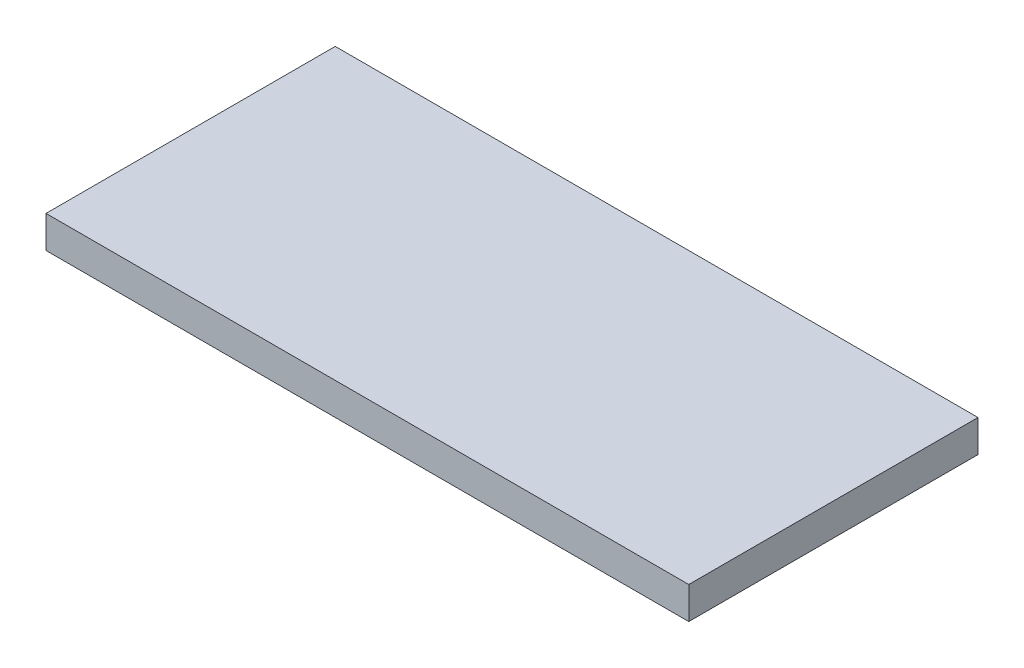
SolidWorks part; units mm, degrees
ref_plane "前视基准面" through (0, 0, 0) normal (0, 0, 1) x (1, 0, 0)
ref_plane "上视基准面" through (0, 0, 0) normal (0, 1, 0) x (1, 0, 0)
ref_plane "右视基准面" through (0, 0, 0) normal (1, 0, 0) x (0, 0, -1)
sketch "草图1" plane through (0, 0, 0) normal (0, 1, 0) x (1, 0, 0)
  line L1 (-50, 22.5) -> (50, 22.5)
  line L2 (-50, 22.5) -> (-50, -22.5)
  line L3 (-50, -22.5) -> (50, -22.5)
  line L4 (50, 22.5) -> (50, -22.5)
  line L5 (-50, 22.5) -> (50, -22.5) construction
  line L6 (-50, -22.5) -> (50, 22.5) construction
  point P0 (0, 0)
  dimension "D1" = 45
  dimension "D2" = 100
extrude "凸台-拉伸1" add sketch "草图1" along normal blind 5
